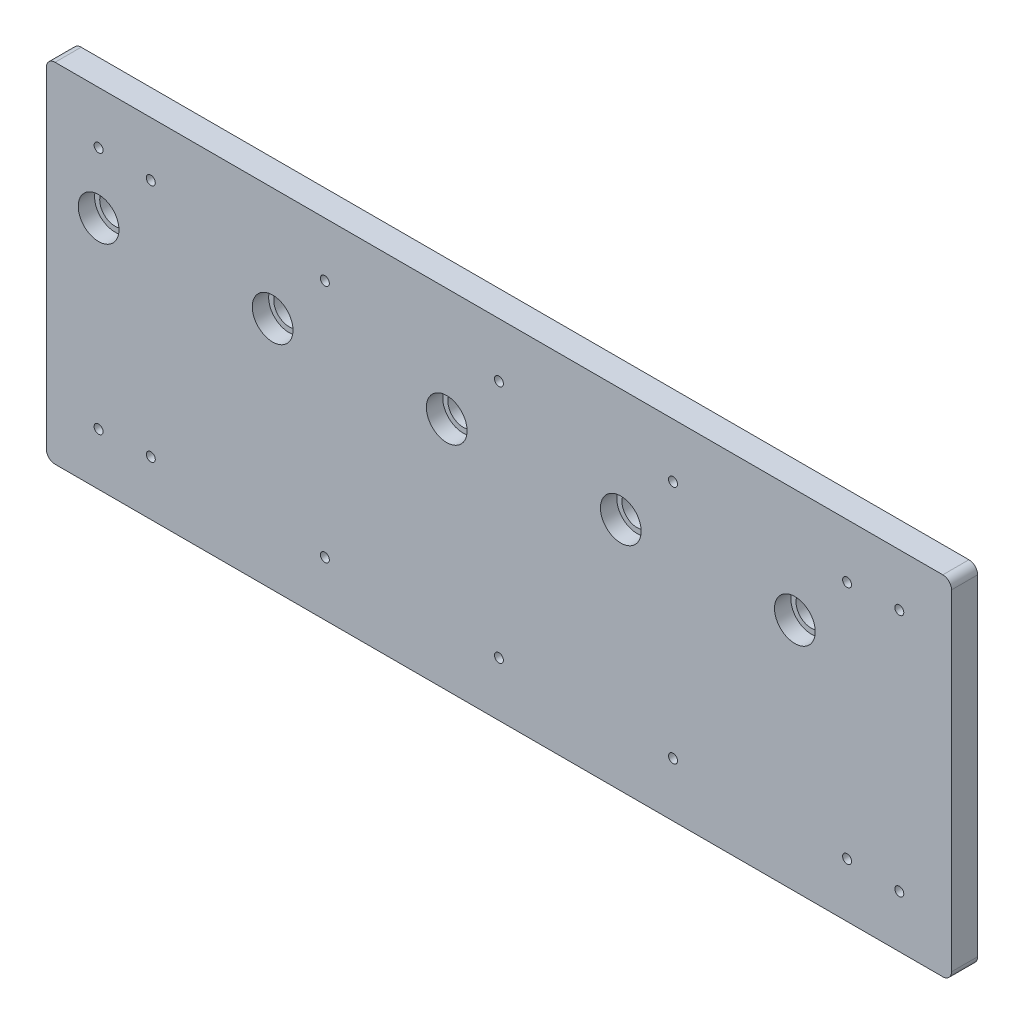
SolidWorks part; units mm, degrees
ref_plane "Front Plane" through (0, 0, 0) normal (0, 0, 1) x (1, 0, 0)
ref_plane "Top Plane" through (0, 0, 0) normal (0, 1, 0) x (1, 0, 0)
ref_plane "Right Plane" through (0, 0, 0) normal (1, 0, 0) x (0, 0, -1)
sketch "Sketch2" plane through (0, 0, 0) normal (0, 0, 1) x (1, 0, 0)
  line L1 (-330.2, -127) -> (330.2, -127)
  line L2 (-330.2, -127) -> (-330.2, 127)
  line L3 (-330.2, 127) -> (330.2, 127)
  line L4 (330.2, -127) -> (330.2, 127)
  line L5 (-330.2, -127) -> (330.2, 127) construction
  line L6 (-330.2, 127) -> (330.2, -127) construction
  point P0 (0, 0)
  dimension "D1" = 660.4
  dimension "D2" = 254
extrude "Boss-Extrude1" add sketch "Sketch2" along normal blind 19.05
hole_wizard "1/4 Clearance Hole1" positions "Sketch3" profile "Sketch4" hole size "1/4" standard "ANSI Inch" end condition up to next
sketch "Sketch3" plane through (0, 0, 19.05) normal (0, 0, 1) x (1, 0, 0)
  line L9 (330.2, -127) -> (330.2, 127) construction
  line L10 (330.2, 127) -> (-330.2, 127) construction
  point P147 (-254, 87.376)
  point P154 (-127, 87.376)
  point P155 (0, 87.376)
  point P156 (127, 87.376)
  point P157 (254, 87.376)
  point P158 (-127, -87.376)
  point P159 (0, -87.376)
  point P160 (127, -87.376)
  point P161 (254, -87.376)
  point P162 (-254, -87.376)
  dimension "D1" = 254
  dimension "D2" = 87.376
  dimension "D3" = 5
  dimension "D4" = 2
sketch "Sketch4" plane through (-254, -87.376, 19.05) normal (1, 0, 0) x (0, -1, 0)
  line L0 (0, 0) -> (0, 19.05)
  line L1 (0, 19.05) -> (3.2639, 19.05)
  line L2 (3.2639, 19.05) -> (3.2639, 0)
  line L5 (3.2639, 0) -> (0, 0)
  line L11 (0, -6.35) -> (0, 107.95) construction
  dimension "Thru Hole Dia." = 6.5278
  dimension "Thru Hole Depth" = 19.05
fillet "Fillet1" radius 6.35 4 edges at (330.2, 127, 9.525) (330.2, -127, 9.525) (-330.2, -127, 9.525) (-330.2, 127, 9.525)
hole_wizard "1/4 Clearance Hole2" positions "Sketch5" profile "Sketch7" hole size "1/4" standard "ANSI Inch" end condition through all
sketch "Sketch5" plane through (0, 0, 19.05) normal (0, 0, 1) x (1, 0, 0)
  line L3 (-292.1, 88.9) -> (292.1, 88.9) construction
  line L4 (-292.1, 88.9) -> (-292.1, -88.9) construction
  line L5 (-292.1, -88.9) -> (292.1, -88.9) construction
  line L6 (292.1, 88.9) -> (292.1, -88.9) construction
  line L7 (323.85, 127) -> (-323.85, 127) construction
  line L8 (-330.2, 120.65) -> (-330.2, -120.65) construction
  line L9 (-323.85, -127) -> (323.85, -127) construction
  line L10 (330.2, -120.65) -> (330.2, 120.65) construction
  point P0 (-292.1, 88.9)
  point P16 (292.1, -88.9)
  point P77 (-292.1, -88.9)
  point P78 (292.1, 88.9)
  dimension "D1" = 38.1
  dimension "D2" = 38.1
  dimension "D3" = 38.1
  dimension "D4" = 38.1
sketch "Sketch7" plane through (-292.1, 88.9, 19.05) normal (1, 0, 0) x (0, -1, 0)
  line L0 (0, 0) -> (0, 19.05)
  line L1 (0, 19.05) -> (3.2639, 19.05)
  line L2 (3.2639, 19.05) -> (3.2639, 0)
  line L5 (3.2639, 0) -> (0, 0)
  line L11 (0, -6.35) -> (0, 107.95) construction
  dimension "Thru Hole Dia." = 6.5278
  dimension "Thru Hole Depth" = 19.05
sketch "Sketch10" plane through (0, 0, 0) normal (0, 0, -1) x (-1, 0, 0)
  line L0 (-330.2, -120.65) -> (-330.2, 120.65) construction
  line L1 (-323.85, 127) -> (323.85, 127) construction
  circle A0 centre (-215.9, 44.45) radius 11.1125
  circle A1 centre (-88.9, 44.45) radius 11.1125
  circle A2 centre (38.1, 44.45) radius 11.1125
  circle A3 centre (165.1, 44.45) radius 11.1125
  circle A4 centre (292.1, 44.45) radius 11.1125
  dimension "D1" = 114.3
  dimension "D2" = 82.55
  dimension "D3" = 22.225
  dimension "D4" = 5
extrude "Cut-Extrude1" cut sketch "Sketch10" against normal through all
sketch "Sketch12" plane through (0, 0, 19.05) normal (0, 0, 1) x (1, 0, 0)
  circle A0 centre (-292.1, 44.45) radius 14.859
  circle A1 centre (-165.1, 44.45) radius 14.859
  circle A2 centre (-38.1, 44.45) radius 14.859
  circle A3 centre (88.9, 44.45) radius 14.859
  circle A4 centre (215.9, 44.45) radius 14.859
  dimension "D1" = 29.718
  dimension "D2" = 5
extrude "Cut-Extrude2" cut sketch "Sketch12" against normal blind 11.938
